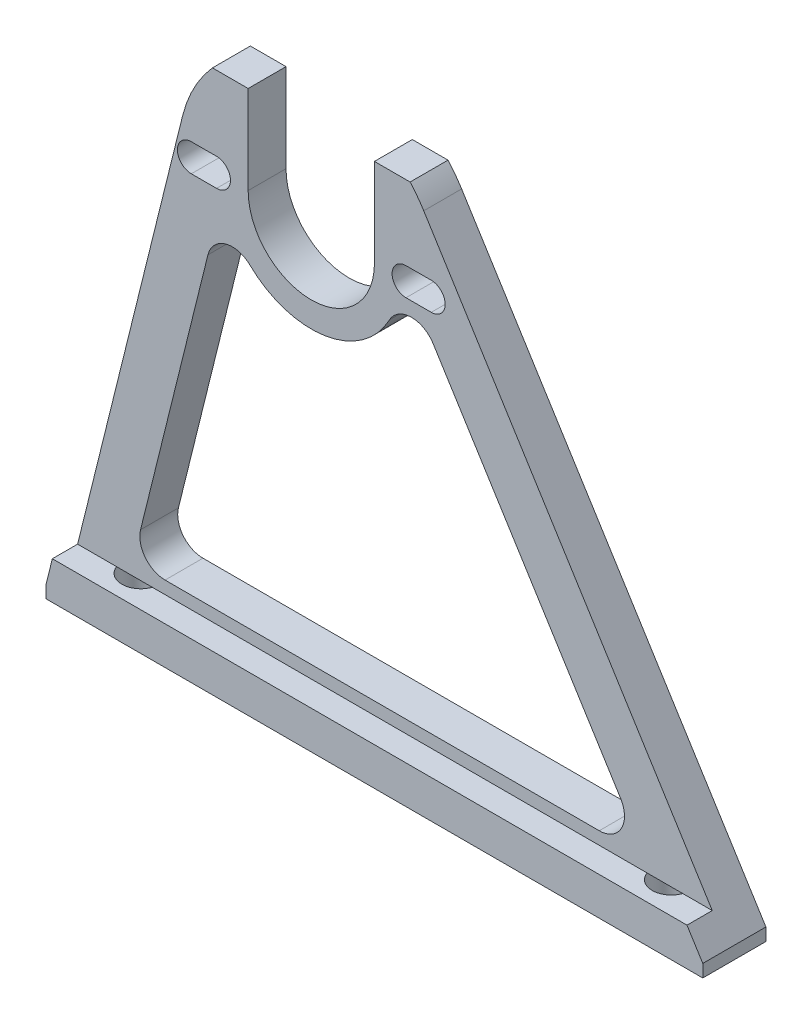
SolidWorks part; units mm, degrees
ref_plane "前视基准面" through (0, 0, 0) normal (0, 0, 1) x (1, 0, 0)
ref_plane "上视基准面" through (0, 0, 0) normal (0, 1, 0) x (1, 0, 0)
ref_plane "右视基准面" through (0, 0, 0) normal (1, 0, 0) x (0, 0, -1)
sketch "草图1" plane through (0, 0, 0) normal (0, 0, 1) x (1, 0, 0)
  line L0 (-10.1914, 2.5269) -> (-19, -33)
  line L1 (-8.4527, -7.0818) -> (-13.5198, -27.5187)
  line L2 (33, -33) -> (8.9047, 5.5638)
  line L3 (-19, -33) -> (-19, -34)
  line L4 (-19, -34) -> (33, -34)
  line L5 (33, -34) -> (33, -33)
  line L6 (-11.5786, -30) -> (22.801, -30)
  line L7 (24.4972, -26.9402) -> (9.6425, -3.1658)
  line L8 (-8.4527, -7.0818) -> (-8.1847, -6.0009)
  line L9 (-7.8262, 7) -> (-5, 7)
  line L10 (-5, 0) -> (-5, 7)
  line L11 (5, 0) -> (5, 7)
  line L12 (-9.5, 1.1) -> (-7.5, 1.1)
  line L13 (-9.5, -1.1) -> (-7.5, -1.1)
  line L14 (0, 0) -> (0, 4.1521) construction
  line L15 (9.5, -1.1) -> (7.5, -1.1)
  line L16 (9.5, 1.1) -> (7.5, 1.1)
  line L17 (5, 7) -> (7.8262, 7)
  arc A0 (8.9047, 5.5638) -> (7.8262, 7) centre (0, 0) ccw
  arc A1 (-4.856, -5.0417) -> (6.1805, -3.2865) centre (0, 0) ccw
  arc A2 (22.801, -30) -> (24.4972, -26.9402) centre (22.801, -28) ccw
  arc A3 (-11.5786, -30) -> (-13.5198, -27.5187) centre (-11.5786, -28) cw
  arc A4 (-8.1847, -6.0009) -> (-4.856, -5.0417) centre (-6.2435, -6.4822) cw
  arc A5 (9.6425, -3.1658) -> (6.1805, -3.2865) centre (7.9464, -4.2255) ccw
  arc A6 (-5, 0) -> (5, 0) centre (0, 0) ccw
  arc A7 (9.5, 1.1) -> (9.5, -1.1) centre (9.5, 0) cw
  arc A8 (-9.5, 1.1) -> (-9.5, -1.1) centre (-9.5, 0) ccw
  arc A9 (7.5, -1.1) -> (7.5, 1.1) centre (7.5, 0) cw
  arc A10 (-7.5, -1.1) -> (-7.5, 1.1) centre (-7.5, 0) ccw
  arc A11 (-7.8262, 7) -> (-10.1914, 2.5269) centre (0, 0) ccw
  dimension "D1" = 14
  dimension "D2" = 21
  dimension "D9" = 2
  dimension "D10" = 2
  dimension "D13" = 10
  dimension "D16" = 1.1
  dimension "D17" = 2
  dimension "D3" = 4
  dimension "D4" = 19
  dimension "D5" = 52
  dimension "D6" = 1
  dimension "D7" = 4
  dimension "D8" = 4
  dimension "D11" = 34
  dimension "D12" = 1
  dimension "D14" = 41
  dimension "D15" = 7.5
  dimension "D18" = 15
extrude "凸台-拉伸1" add sketch "草图1" along normal blind 5
sketch "草图2" plane through (0, 0, 5) normal (0, 0, 1) x (1, 0, 0)
  line L0 (-19, -34) -> (33, -34) construction
  line L1 (54.2962, -31) -> (-51.2945, -31)
  line L2 (54.2962, -31) -> (54.2962, 22.7343)
  line L3 (54.2962, 22.7343) -> (-51.2945, 22.7343)
  line L4 (-51.2945, -31) -> (-51.2945, 22.7343)
  line L5 (54.2962, -31) -> (-51.2945, 22.7343) construction
  line L6 (54.2962, 22.7343) -> (-51.2945, -31) construction
  point P0 (1.5009, -4.1328)
  dimension "D1" = 3
extrude "切除-拉伸1" cut sketch "草图2" against normal blind 2
sketch "草图4" plane through (0, -34, 0) normal (0, -1, 0) x (-1, 0, 0)
  line L0 (19, -2.5) -> (-33, -2.5) construction
  line L1 (19, -5) -> (19, 0) construction
  line L2 (-33, -5) -> (-33, 0) construction
  circle A0 centre (14, -2.5) radius 1.5
  circle A1 centre (-28, -2.5) radius 1.5
  dimension "D1" = 3
  dimension "D2" = 3
  dimension "D3" = 42
  dimension "D4" = 5
extrude "切除-拉伸2" cut sketch "草图4" against normal blind 3
